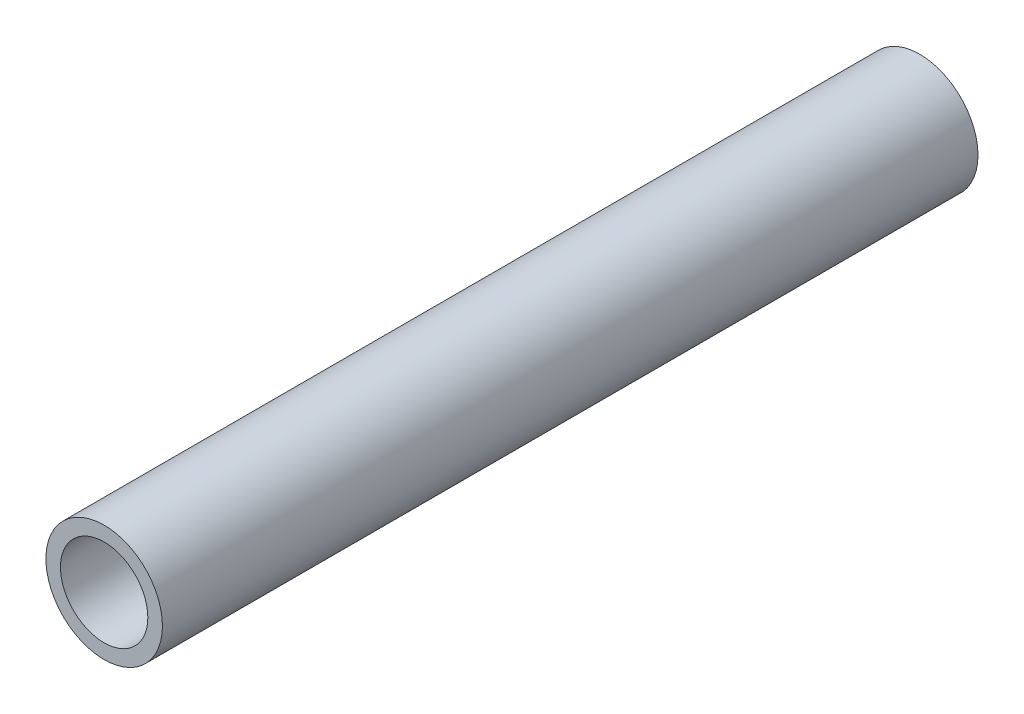
SolidWorks part; units mm, degrees
ref_plane "Front Plane" through (0, 0, 0) normal (0, 0, 1) x (1, 0, 0)
ref_plane "Top Plane" through (0, 0, 0) normal (0, 1, 0) x (1, 0, 0)
ref_plane "Right Plane" through (0, 0, 0) normal (1, 0, 0) x (0, 0, -1)
sketch "Sketch1" plane through (0, 0, 0) normal (0, 0, 1) x (1, 0, 0)
  circle A0 centre (0, 0) radius 20
  dimension "D1" = 40
extrude "Boss-Extrude1" add sketch "Sketch1" along normal blind 280
sketch "Sketch2" plane through (0, 0, 280) normal (0, 0, 1) x (1, 0, 0)
  circle A0 centre (0, 0) radius 15
  dimension "D1" = 30
extrude "Cut-Extrude1" cut sketch "Sketch2" against normal through all
